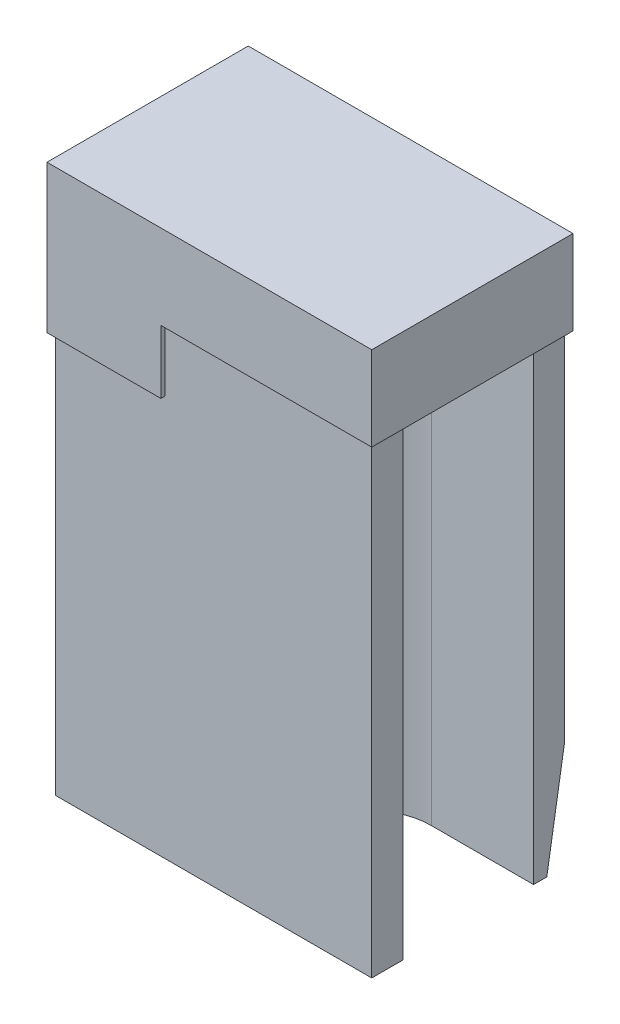
SolidWorks part; units mm, degrees
ref_plane "Front" through (0, 0, 0) normal (0, 0, 1) x (1, 0, 0)
ref_plane "Top" through (0, 0, 0) normal (0, 1, 0) x (1, 0, 0)
ref_plane "Right" through (0, 0, 0) normal (1, 0, 0) x (0, 0, -1)
sketch "Sketch1" plane through (0, 0, 0) normal (0, 1, 0) x (1, 0, 0)
  line L0 (0, 0) -> (-50.8, 0) construction
  line L1 (-50.8, 22.86) -> (24.2, 22.86)
  line L2 (-50.8, 22.86) -> (-50.8, -22.86)
  line L3 (-50.8, -22.86) -> (24.2, -22.86)
  line L4 (24.2, 22.86) -> (24.2, 15.5)
  line L5 (0, 15.5) -> (24.2, 15.5)
  line L6 (0, -15.5) -> (24.2, -15.5)
  line L7 (24.2, -15.5) -> (24.2, -22.86)
  arc A1 (0, 15.5) -> (0, -15.5) centre (0, 0) ccw
  dimension "D1" = 31
  dimension "D2" = 50.8
  dimension "D3" = 45.72
  dimension "D4" = 75
extrude "Boss-Extrude1" add sketch "Sketch1" along normal blind 95
sketch "Sketch2" plane through (24.2, 0, 0) normal (1, 0, 0) x (0, 0, -1)
  line L0 (22.86, 0) -> (18.6436, 0)
  line L1 (15.5, 0) -> (22.86, 0) construction
  line L2 (18.6436, 0) -> (22.86, 25.5524)
  line L3 (22.86, 95) -> (22.86, 0) construction
  line L4 (22.86, 25.5524) -> (22.86, 0)
  dimension "D1" = 4.2164
  dimension "D2" = 25.5524
extrude "Cut-Extrude1" cut sketch "Sketch2" against normal through all
sketch "Sketch3" plane through (0, 95, 0) normal (0, 1, 0) x (1, 0, 0)
  line L0 (24.2, 22.86) -> (-50.8, 22.86) construction
  line L1 (24.2, 22.86) -> (-50.8, 22.86)
  line L2 (-50.8, -22.86) -> (24.2, -22.86) construction
  line L3 (24.2, -22.86) -> (24.2, -15.5) construction
  line L4 (24.2, -15.5) -> (0, -15.5) construction
  line L5 (0, 15.5) -> (24.2, 15.5) construction
  line L6 (24.2, 15.5) -> (24.2, 22.86) construction
  line L7 (-50.8, -22.86) -> (24.2, -22.86)
  line L8 (24.2, -22.86) -> (24.2, -15.5)
  line L9 (24.2, -15.5) -> (0, -15.5)
  line L10 (0, 15.5) -> (24.2, 15.5)
  line L11 (24.2, 15.5) -> (24.2, 22.86)
  line L12 (-24.8, 22.86) -> (-24.8, -22.86)
  arc A0 (0, 15.5) -> (0, -15.5) centre (0, 0) ccw construction
  arc A1 (0, 15.5) -> (0, -15.5) centre (0, 0) ccw
  point P11 (24.2, 19.18)
  line M3 (24.2, -22.86) -> (24.2, -15.5)
  line M4 (24.2, -15.5) -> (0, -15.5)
  arc M5 (0, -15.5) -> (0, 15.5) centre (0, 0) cw
  line M6 (0, 15.5) -> (24.2, 15.5)
  line M7 (24.2, 15.5) -> (24.2, 22.86)
  line M8 (24.2, 22.86) -> (-50.8, 22.86)
  dimension "D1" = 49
extrude "Boss-Extrude2" add sketch "Sketch3" along normal blind 15 contours L12 L7 M8 M3 M4 M5 M6 M7
sketch "Sketch4" plane through (0, 110, 0) normal (0, 1, 0) x (1, 0, 0)
  line L0 (24.2, 22.86) -> (-24.8, 22.86) construction
  line L1 (25.2, 23.86) -> (-24.8, 23.86)
  line L2 (25.2, 23.86) -> (25.2, -23.86)
  line L3 (25.2, -23.86) -> (-24.8, -23.86)
  line L4 (-24.8, 23.86) -> (-24.8, -23.86)
  line L5 (-24.8, -22.86) -> (24.2, -22.86) construction
  line L7 (-24.8, 22.86) -> (-24.8, -22.86) construction
  line L8 (24.2, 15.5) -> (24.2, 22.86) construction
  dimension "D1" = 1
  dimension "D2" = 1
  dimension "D3" = 1
extrude "Boss-Extrude3" add sketch "Sketch4" along normal blind 20
sketch "Sketch5" plane through (0, 95, 0) normal (0, 1, 0) x (1, 0, 0)
  line L0 (-24.8, 23.86) -> (-51.8, 23.86)
  line L1 (-51.8, 23.86) -> (-51.8, -23.86)
  line L2 (-24.8, -23.86) -> (-51.8, -23.86)
  line L3 (-50.8, 22.86) -> (-50.8, -22.86) construction
  line L4 (-24.8, 23.86) -> (-24.8, -23.86)
  dimension "D1" = 1
extrude "Boss-Extrude4" add sketch "Sketch5" along normal up to vertex (35 mm away)
